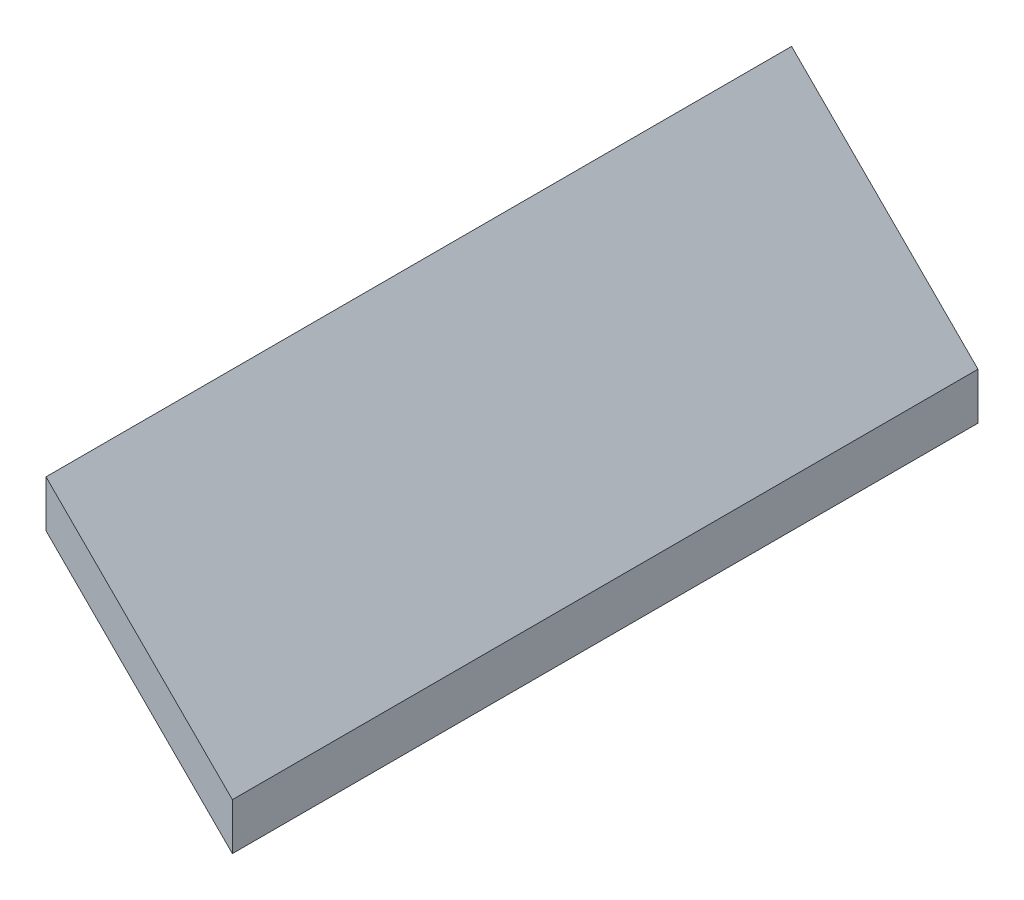
SolidWorks part; units mm, degrees
ref_plane "Front Plane" through (0, 0, 0) normal (0, 0, 1) x (1, 0, 0)
ref_plane "Top Plane" through (0, 0, 0) normal (0, 1, 0) x (1, 0, 0)
ref_plane "Right Plane" through (0, 0, 0) normal (1, 0, 0) x (0, 0, -1)
sketch "Sketch2" plane through (0, 0, 0) normal (0, 0, 1) x (1, 0, 0)
  line L0 (0, 0) -> (0, -4.7752)
  line L1 (0, -4.7752) -> (19.05, -23.8252)
  line L2 (19.05, -23.8252) -> (19.05, -19.05)
  line L3 (19.05, -19.05) -> (0, 0)
  dimension "D1" = 4.7752
  dimension "D2" = 4.7752
  dimension "D3" = 135
  dimension "D4" = 19.05
extrude "Boss-Extrude1" add sketch "Sketch2" along normal blind 76.2
